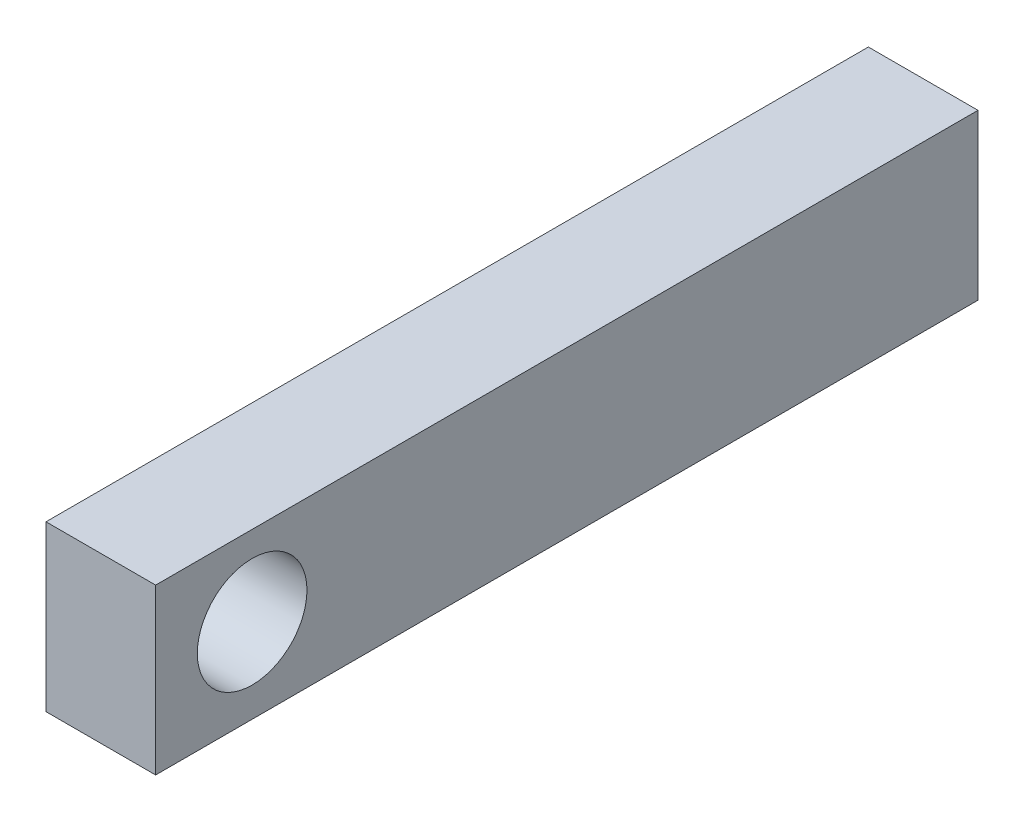
SolidWorks part; units mm, degrees
ref_plane "前视基准面" through (0, 0, 0) normal (0, 0, 1) x (1, 0, 0)
ref_plane "上视基准面" through (0, 0, 0) normal (0, 1, 0) x (1, 0, 0)
ref_plane "右视基准面" through (0, 0, 0) normal (1, 0, 0) x (0, 0, -1)
sketch "草图1" plane through (0, 0, 0) normal (0, 1, 0) x (1, 0, 0)
  line L1 (-26.1053, 8.4211) -> (-24.1053, 8.4211)
  line L2 (-26.1053, 8.4211) -> (-26.1053, -6.5789)
  line L3 (-26.1053, -6.5789) -> (-24.1053, -6.5789)
  line L4 (-24.1053, 8.4211) -> (-24.1053, -6.5789)
extrude "凸台-拉伸2" add sketch "草图1" along normal blind 3
sketch "草图2" plane through (0, 0, 0) normal (1, 0, 0) x (0, 0, -1)
  circle A0 centre (-4.8187, 1.5408) radius 1
extrude "切除-拉伸1" cut sketch "草图2" against normal through all contours A0
